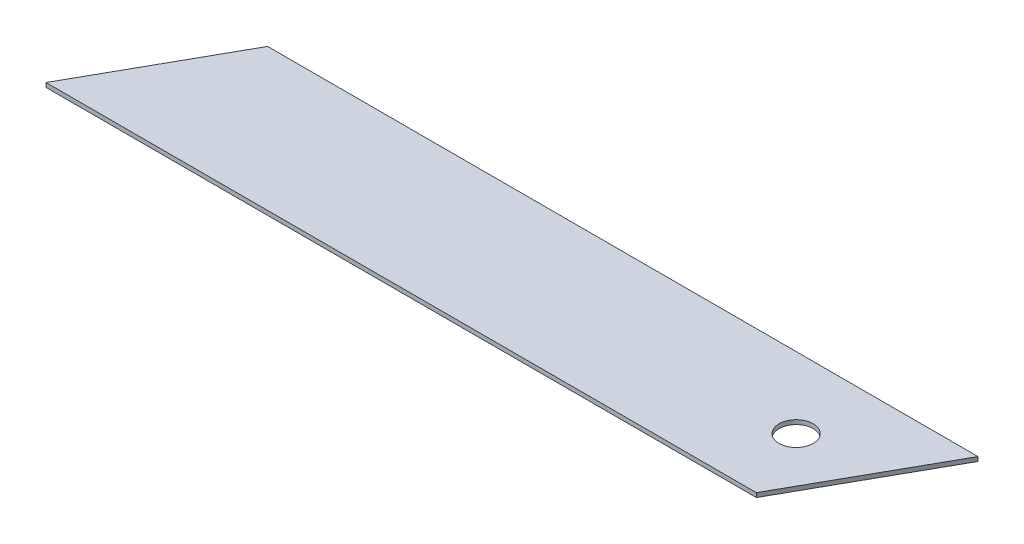
SolidWorks part; units mm, degrees
ref_plane "Front Plane" through (0, 0, 0) normal (0, 0, 1) x (1, 0, 0)
ref_plane "Top Plane" through (0, 0, 0) normal (0, 1, 0) x (1, 0, 0)
ref_plane "Right Plane" through (0, 0, 0) normal (1, 0, 0) x (0, 0, -1)
sketch "Sketch1" plane through (0, 0, 0) normal (0, 1, 0) x (1, 0, 0)
  line L0 (14.224, 25.4) -> (0, 0)
  line L1 (0, 0) -> (127, 0)
  line L3 (14.224, 25.4) -> (141.224, 25.4)
  line L5 (141.224, 25.4) -> (127, 0)
  line L6 (127, 0) -> (127, 25.4) construction
  line L7 (121.412, 12.7) -> (134.112, 12.7) construction
  circle A0 centre (121.412, 12.7) radius 3.048
  dimension "D1" = 6.096
  dimension "D6" = 12.7
  dimension "D7" = 0
  dimension "D2" = 12.7
  dimension "D3" = 12.7
  dimension "D4" = 127
  dimension "D5" = 14.224
  dimension "D8" = 12.7
extrude "Boss-Extrude1" add sketch "Sketch1" along normal blind 0.762
